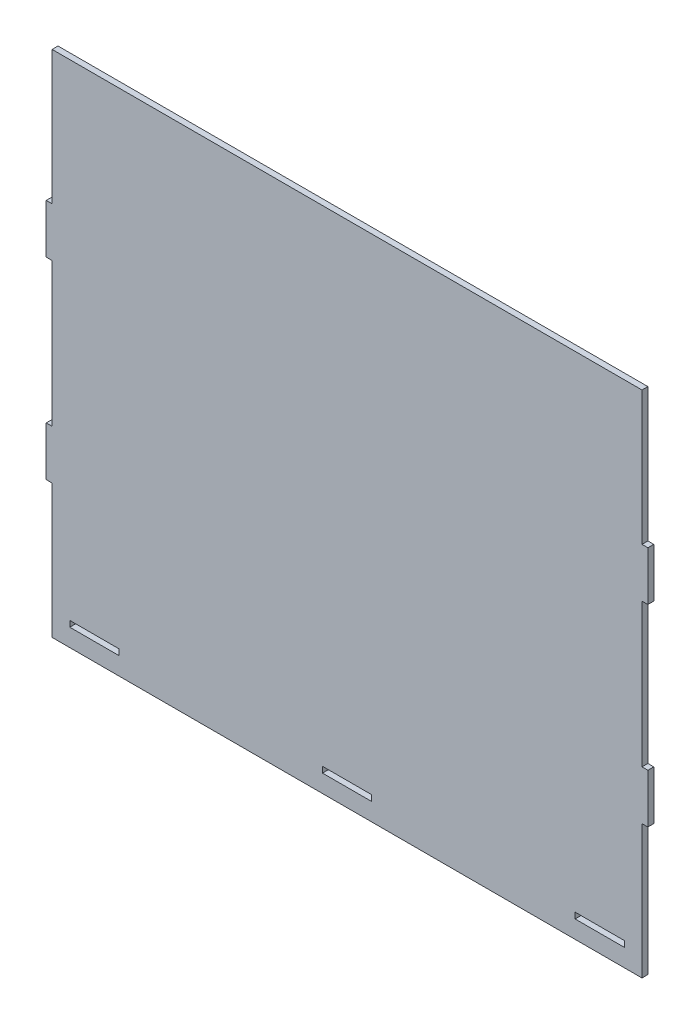
SolidWorks part; units mm, degrees
material "Maple"
ref_plane "Front Plane" through (0, 0, 0) normal (0, 0, 1) x (1, 0, 0)
ref_plane "Top Plane" through (0, 0, 0) normal (0, 1, 0) x (1, 0, 0)
ref_plane "Right Plane" through (0, 0, 0) normal (1, 0, 0) x (0, 0, -1)
sketch "Sketch1" plane through (0, 0, 0) normal (0, 0, 1) x (1, 0, 0)
  line L0 (-514, 0) -> (0, 0) construction
  line L1 (-300, 259) -> (300, 259)
  line L2 (-300, 259) -> (-300, 123)
  line L3 (-300, -259) -> (300, -259)
  line L4 (300, 259) -> (300, 123)
  line L5 (-300, 259) -> (300, -259) construction
  line L6 (-300, -259) -> (300, 259) construction
  line L7 (-306, 123) -> (-300, 123)
  line L8 (-306, 123) -> (-306, 73)
  line L9 (-306, 73) -> (-300, 73)
  line L11 (-300, 207) -> (-282.5, 182) construction
  line L12 (-300, -123) -> (-300, -259)
  line L13 (0, 259) -> (0, -259) construction
  line L14 (306, 73) -> (300, 73)
  line L15 (306, 123) -> (306, 73)
  line L16 (306, 123) -> (300, 123)
  line L17 (306, -73) -> (300, -73)
  line L18 (306, -123) -> (300, -123)
  line L19 (306, -123) -> (306, -73)
  line L20 (-306, -73) -> (-300, -73)
  line L22 (-306, -123) -> (-300, -123)
  line L23 (-306, -123) -> (-306, -73)
  line L24 (-300, 73) -> (-300, -73)
  line L25 (300, -123) -> (300, -259)
  line L26 (300, 73) -> (300, -73)
  line L27 (-257, 0) -> (-257, -259) construction
  line L28 (282, -241) -> (232, -241)
  line L29 (-282, -235) -> (-232, -235)
  line L30 (-282, -235) -> (-282, -241)
  line L31 (-282, -241) -> (-232, -241)
  line L32 (-232, -235) -> (-232, -241)
  line L33 (-282, -235) -> (-232, -241) construction
  line L34 (-282, -241) -> (-232, -235) construction
  line L35 (232, -235) -> (232, -241)
  line L36 (282, -235) -> (232, -235)
  line L37 (282, -235) -> (282, -241)
  line L39 (-25, -235) -> (25, -235)
  line L40 (-25, -235) -> (-25, -241)
  line L41 (-25, -241) -> (25, -241)
  line L42 (25, -235) -> (25, -241)
  line L43 (-25, -235) -> (25, -241) construction
  line L44 (-25, -241) -> (25, -235) construction
  point P0 (0, 0)
  point P6 (-300, 207)
  point P31 (-257, -238)
  point P40 (0, -238)
  dimension "D1" = 600
  dimension "D2" = 518
  dimension "D3" = 136
  dimension "D4" = 50
  dimension "D5" = 50
  dimension "D6" = 6
  dimension "D7" = 18
  dimension "D8" = 136
  dimension "D9" = 136
  dimension "D10" = 136
  dimension "D11" = 18
  dimension "D12" = 50
  dimension "D13" = 6
  dimension "D14" = 18
  dimension "D15" = 6
extrude "Boss-Extrude1" add sketch "Sketch1" along normal blind 6
